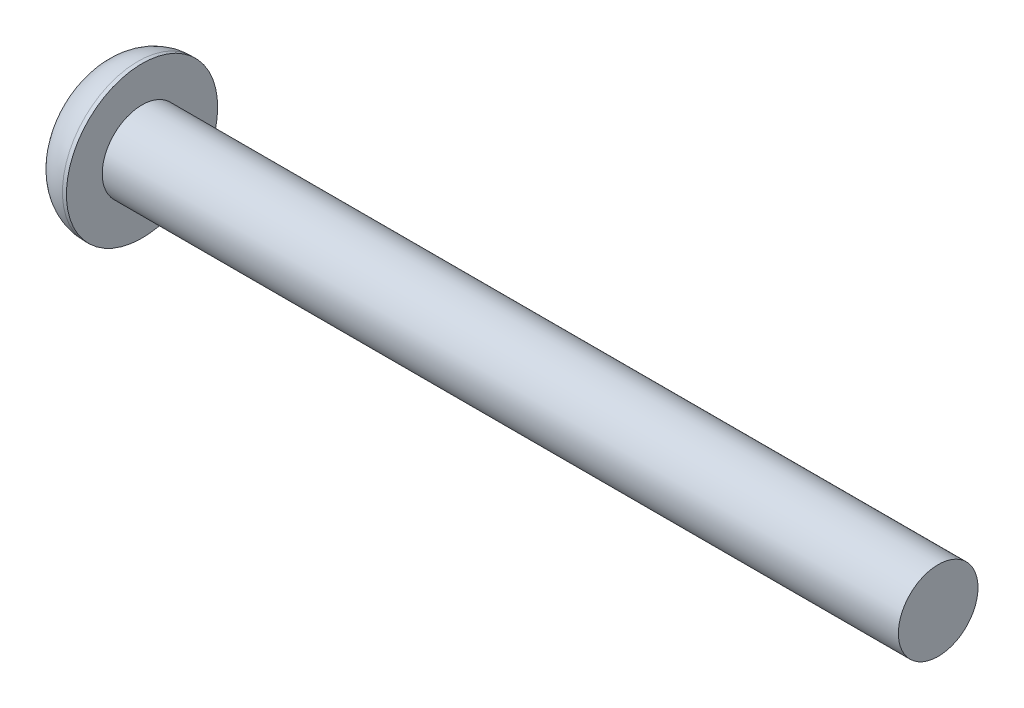
SolidWorks part; units mm, degrees
material "AISI 1020"
ref_plane "Front Plane" through (0, 0, 0) normal (0, 0, 1) x (1, 0, 0)
ref_plane "Top Plane" through (0, 0, 0) normal (0, 1, 0) x (1, 0, 0)
ref_plane "Right Plane" through (0, 0, 0) normal (1, 0, 0) x (0, 0, -1)
sketch "Sketch1" plane through (0, 0, 0) normal (0, 1, 0) x (1, 0, 0)
  line L0 (0, 0) -> (31.65, 0)
  line L1 (31.65, 0) -> (31.65, 1.5)
  line L2 (31.65, 1.5) -> (1.65, 1.5)
  line L3 (1.65, 1.5) -> (1.65, 2.85)
  line L4 (1.65, 2.85) -> (1.5, 2.85)
  line L5 (0, 1.35) -> (0, 0)
  line L6 (0, 0) -> (-8.9321, 0) construction
  arc A0 (0, 1.35) -> (1.5, 2.85) centre (1.5, 1.35) cw
  point P11 (0, 2.85)
  dimension "D5" = 1.5
  dimension "D1" = 1.5
  dimension "D2" = 30
  dimension "D3" = 1.65
  dimension "D4" = 2.85
revolve "Revolve1" add sketch "Sketch1" angle 360 about L6
sketch "Sketch2" plane through (0, 0, 0) normal (-1, 0, 0) x (0, 0, 1)
  line L1 (1.1547, 0) -> (0.5774, 1)
  line L2 (0.5774, 1) -> (-0.5774, 1)
  line L3 (-0.5774, 1) -> (-1.1547, 0)
  line L4 (-1.1547, 0) -> (-0.5774, -1)
  line L5 (-0.5774, -1) -> (0.5774, -1)
  line L6 (0.5774, -1) -> (1.1547, 0)
  circle A0 centre (0, 0) radius 1 construction
  dimension "D1" = 2
extrude "Cut-Extrude1" cut sketch "Sketch2" against normal blind 1.04
